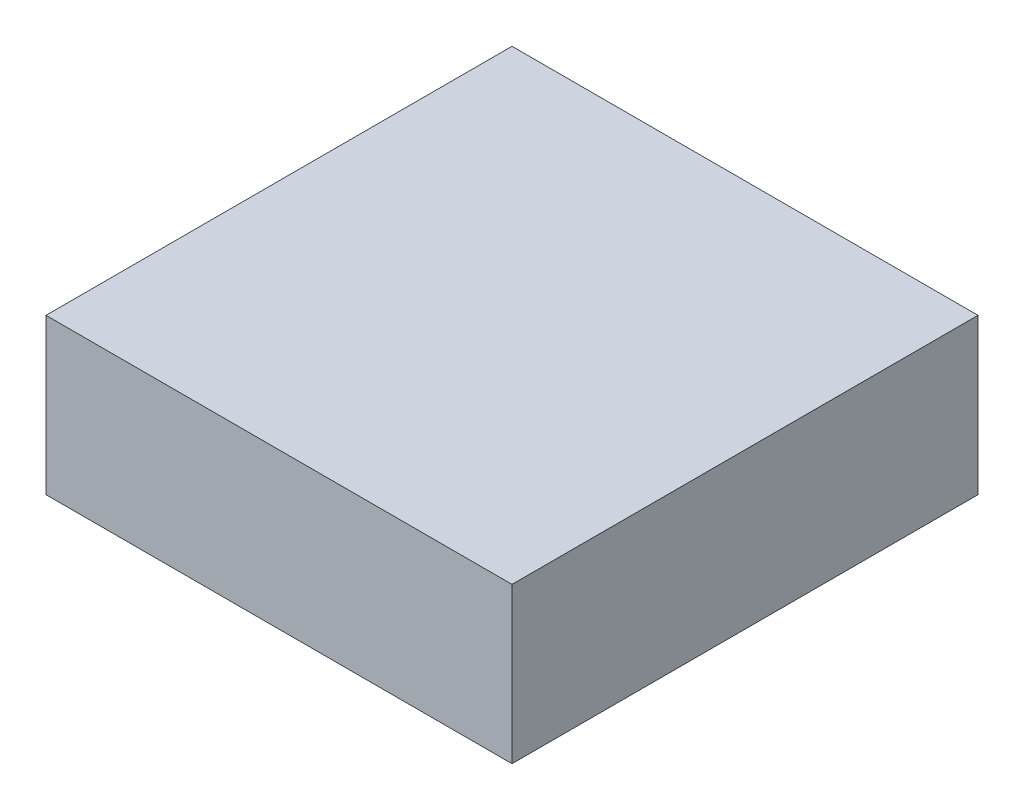
SolidWorks part; units mm, degrees
ref_plane "Front Plane" through (0, 0, 0) normal (0, 0, 1) x (1, 0, 0)
ref_plane "Top Plane" through (0, 0, 0) normal (0, 1, 0) x (1, 0, 0)
ref_plane "Right Plane" through (0, 0, 0) normal (1, 0, 0) x (0, 0, -1)
sketch "Sketch1" plane through (0, 0, 0) normal (0, 1, 0) x (1, 0, 0)
  line L1 (-6.3, -6.3) -> (6.3, -6.3)
  line L2 (-6.3, -6.3) -> (-6.3, 6.3)
  line L3 (-6.3, 6.3) -> (6.3, 6.3)
  line L4 (6.3, -6.3) -> (6.3, 6.3)
  line L5 (-6.3, -6.3) -> (6.3, 6.3) construction
  line L6 (-6.3, 6.3) -> (6.3, -6.3) construction
  point P0 (0, 0)
  dimension "D1" = 12.6
extrude "Boss-Extrude1" add sketch "Sketch1" along normal blind 4.2
